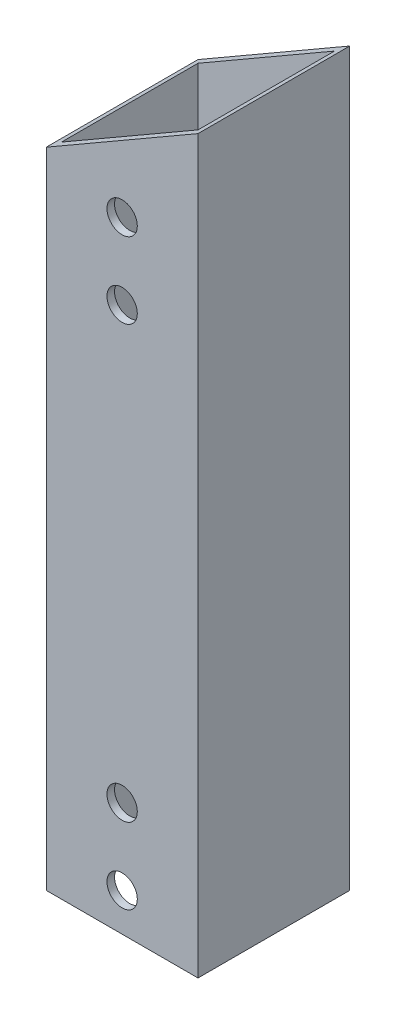
SolidWorks part; units mm, degrees
ref_plane "前视基准面" through (0, 0, 0) normal (0, 0, 1) x (1, 0, 0)
ref_plane "上视基准面" through (0, 0, 0) normal (0, 1, 0) x (1, 0, 0)
ref_plane "右视基准面" through (0, 0, 0) normal (1, 0, 0) x (0, 0, -1)
sketch "草图1" plane through (0, 0, 0) normal (0, 0, 1) x (1, 0, 0)
  line L0 (5.6571, 25.7475) -> (25.6571, 37.2945)
  line L1 (5.6571, -59.088) -> (25.6571, -59.088)
  line L2 (25.6571, -59.088) -> (25.6571, 37.2945)
  line L3 (25.6571, 37.2945) -> (5.6571, 25.7475)
  line L4 (5.6571, 25.7475) -> (5.6571, -59.088)
  circle A1 centre (15.6571, -54.088) radius 2
  circle A2 centre (15.6571, -44.088) radius 2
  circle A3 centre (15.6571, 12.7475) radius 2
  circle A4 centre (15.6571, 22.7475) radius 2
extrude "凸台-拉伸1" add sketch "草图1" along normal blind 20 contours L0 L4 L1 L2 A4 A3 A2 A1
sketch "草图2" plane through (0, -59.088, 0) normal (0, -1, 0) x (1, 0, 0)
  line L0 (15.6571, 0) -> (15.6571, 20) construction
  line L1 (5.6571, 0) -> (25.6571, 0) construction
  line L2 (5.6571, 20) -> (25.6571, 20) construction
  line L4 (6.6571, 19) -> (24.6571, 19)
  line L5 (6.6571, 19) -> (6.6571, 1)
  line L6 (6.6571, 1) -> (24.6571, 1)
  line L7 (24.6571, 19) -> (24.6571, 1)
  line L8 (15.6571, 1) -> (15.6571, 19) construction
  line L9 (6.6571, 10) -> (24.6571, 10) construction
  point P6 (15.6571, 10)
  dimension "D1" = 18
  dimension "D2" = 18
extrude "切除-拉伸1" cut sketch "草图2" against normal through all
